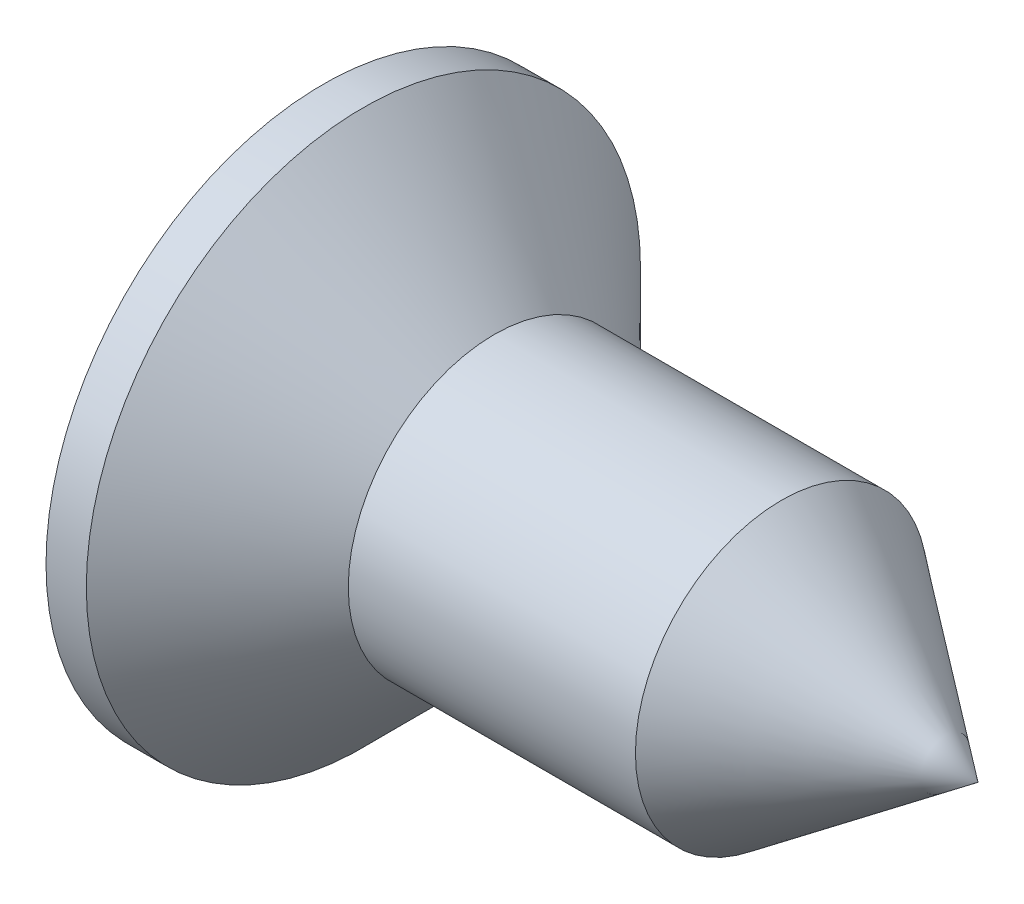
SolidWorks part; units mm, degrees
ref_plane "Front" through (0, 0, 0) normal (0, 0, 1) x (1, 0, 0)
ref_plane "Top" through (0, 0, 0) normal (0, 1, 0) x (1, 0, 0)
ref_plane "Right" through (0, 0, 0) normal (1, 0, 0) x (0, 0, -1)
sketch "Sketch1" plane through (0, 0, 0) normal (0, 0, 1) x (1, 0, 0)
  line L0 (0, 2.75) -> (0.4, 2.75)
  line L1 (0.4, 2.75) -> (1.7, 1.45)
  line L2 (1.7, 1.45) -> (6.5, 1.45)
  line L3 (6.5, 1.45) -> (6.5, 0)
  line L4 (6.5, 0) -> (0, 0)
  line L5 (0, 0) -> (0, 2.75)
  line L6 (6.6207, 0) -> (-0.9387, 0) construction
  dimension "D1" = 45
  dimension "d" = 2.9
  dimension "dK" = 5.5
  dimension "l" = 6.5
  dimension "k" = 1.7
revolve "Revolve1" add sketch "Sketch1" angle 360 about L6
cosmetic thread "ThreadCosmetic" [suppressed] parameters "D2"=2.18
chamfer "Chamfer1" distance 0.29 angle 60 1 edges at (6.5, 0, -1.45)
sketch "Sketch9" plane through (0, 0, 0) normal (0, 0, 1) x (1, 0, 0)
  line L0 (2.7022, 1.09) -> (2.0178, 1.09)
  line L1 (2.0178, 1.09) -> (1.81, 1.45)
  line L2 (2.7022, 1.09) -> (2.91, 1.45)
  line L3 (1.81, 1.45) -> (1.81, 1.7)
  line L4 (2.91, 1.45) -> (2.91, 1.7)
  line L5 (1.81, 1.7) -> (2.91, 1.7)
  line L6 (2.36, 1.09) -> (2.36, 0) construction
  line L7 (0, 0) -> (7.3035, 0) construction
  line L8 (1.7, 1.45) -> (1.7, -1.45) construction
  line L9 (5.9977, 1.45) -> (1.7, 1.45) construction
  dimension "D2" = 60
  dimension "D3" = 0.25
  dimension "advance" = 1.1
  dimension "minordia" = 2.18
  dimension "threadstart" = 0.66
revolve "ThreadSchematic" [suppressed] cut sketch "Sketch9" angle 360 about L7
pattern_linear "ThdSchPat" [suppressed] count 5 spacing 1.1 along (-1, 0, 0)
sketch "Sketch3" plane through (0, 0, 0) normal (0, 0, 1) x (1, 0, 0)
  line L0 (1.7, 1.45) -> (6.5, 1.45) construction
  line L2 (3.9, 1.45) -> (4.55, 1.45) construction
  line L3 (6.5, 1.45) -> (6.5, 0) construction
  line L4 (4.55, 1.45) -> (6.5, 1.45)
  line L5 (2.9, 0) -> (5.4301, 0) construction
  line L6 (6.5, 0) -> (6.7, 0)
  line L7 (6.7, 0) -> (6.7, 1.45)
  line L8 (6.7, 1.45) -> (6.5, 1.45)
  line L9 (4.55, 1.45) -> (6.5, 0)
  dimension "y" = 2.6
  dimension "D1" = 0.65
revolve "EndCone" cut sketch "Sketch3" angle 360 about L5
sketch "Sketch4" plane through (0, 0, 0) normal (-1, 0, 0) x (0, 0, 1)
  line L0 (-0.4, 1.6) -> (-0.4, 0.4)
  line L1 (-0.4, 1.6) -> (0.4, 1.6)
  line L2 (-1.6, 0.4) -> (-1.6, -0.4)
  line L3 (-0.4, -1.6) -> (0.4, -1.6)
  line L4 (1.6, 0.4) -> (1.6, -0.4)
  line L5 (0.4, 1.6) -> (0.4, 0.4)
  line L6 (0.4, 0.4) -> (1.6, 0.4)
  line L7 (0.4, -0.4) -> (1.6, -0.4)
  line L8 (0.4, -0.4) -> (0.4, -1.6)
  line L9 (-0.4, -0.4) -> (-0.4, -1.6)
  line L10 (-0.4, -0.4) -> (-1.6, -0.4)
  line L11 (-0.4, 0.4) -> (-1.6, 0.4)
  line L12 (1.6, 0) -> (-1.6, 0) construction
  dimension "m" = 3.2
  dimension "D1" = 0.8
extrude "Cut-Extrude1" cut sketch "Sketch4" against normal blind 1.5
draft "Draft1" type of draft neutral plane draft angle 35 faces to draft 4 face at (0.75, 0, 1.6) face at (0.75, 1.6, 0) face at (0.75, 0, -1.6) face at (0.75, -1.6, 0) neutral plane through (0, 0, 0) neutral plane normal (-1, 0, 0) parameters "D1"=35
draft "Draft2" type of draft neutral plane draft angle 8 faces to draft 8 face at (0.75, -0.7374, -0.4) face at (0.75, -0.4, -0.7374) face at (0.75, -0.4, 0.7374) face at (0.75, -0.7374, 0.4) face at (0.75, 0.7374, 0.4) face at (0.75, 0.4, 0.7374) face at (0.75, 0.4, -0.7374) face at (0.75, 0.7374, -0.4) neutral plane through (0, 0, 0) neutral plane normal (-1, 0, 0) parameters "D1"=8
sketch "Sketch6" plane through (1.5, 0, 0) normal (-1, 0, 0) x (0, 0, 1)
  line L0 (0.1892, 0.1892) -> (0.1892, 0.5497) construction
  line L1 (0.5497, 0.1892) -> (0.1892, 0.1892) construction
  line L2 (-0.1892, 0.5497) -> (-0.1892, 0.1892) construction
  line L3 (-0.1892, 0.1892) -> (-0.5497, 0.1892) construction
  line L4 (-0.5497, -0.1892) -> (-0.1892, -0.1892) construction
  line L5 (-0.1892, -0.1892) -> (-0.1892, -0.5497) construction
  line L6 (0.1892, -0.5497) -> (0.1892, -0.1892) construction
  line L7 (0.1892, -0.1892) -> (0.5497, -0.1892) construction
  line L9 (-0.3694, 0.1892) -> (-0.3694, -0.1892)
  line L10 (-0.1892, -0.3694) -> (0.1892, -0.3694)
  line L11 (0.3694, -0.1892) -> (0.3694, 0.1892)
  line L12 (0.1892, 0.3694) -> (-0.1892, 0.3694)
  arc A0 (0.1892, 0.3694) -> (0.3694, 0.1892) centre (0.3694, 0.3694) ccw
  arc A1 (-0.1892, 0.3694) -> (-0.3694, 0.1892) centre (-0.3694, 0.3694) cw
  arc A2 (-0.3694, -0.1892) -> (-0.1892, -0.3694) centre (-0.3694, -0.3694) cw
  arc A3 (0.1892, -0.3694) -> (0.3694, -0.1892) centre (0.3694, -0.3694) cw
sketch "Sketch7" plane through (0, 0, 0) normal (-1, 0, 0) x (0, 0, 1)
  line L8 (0.4, 0.4) -> (0.4, 1.6) construction
  line L9 (1.6, 0.4) -> (0.4, 0.4) construction
  line L10 (0.4, -0.4) -> (1.6, -0.4) construction
  line L11 (0.4, -1.6) -> (0.4, -0.4) construction
  line L12 (-0.4, 1.6) -> (-0.4, 0.4) construction
  line L13 (-0.4, 0.4) -> (-1.6, 0.4) construction
  line L14 (-1.6, -0.4) -> (-0.4, -0.4) construction
  line L15 (-0.4, -0.4) -> (-0.4, -1.6) construction
  line L16 (0.5802, 0.4) -> (0.5802, -0.4)
  line L17 (0.4, -0.5802) -> (-0.4, -0.5802)
  line L18 (-0.5802, -0.4) -> (-0.5802, 0.4)
  line L19 (-0.4, 0.5802) -> (0.4, 0.5802)
  arc A0 (0.4, 0.5802) -> (0.5802, 0.4) centre (0.5802, 0.5802) ccw
  arc A1 (-0.4, 0.5802) -> (-0.5802, 0.4) centre (-0.5802, 0.5802) cw
  arc A2 (-0.5802, -0.4) -> (-0.4, -0.5802) centre (-0.5802, -0.5802) cw
  arc A3 (0.1892, 0.3694) -> (0.3694, 0.1892) centre (0.3694, 0.3694) ccw construction
  arc A4 (0.5802, -0.4) -> (0.4, -0.5802) centre (0.5802, -0.5802) ccw
loft "Cut-Loft1" cut profiles "Sketch6", "Sketch7"
sketch "Sketch8" plane through (0, 0, 0) normal (-1, 0, 0) x (0, 0, 1)
  line L0 (0, 0) -> (1.6, 1.6) construction
  line L1 (0.1892, 0.3694) -> (1.6, 1.6)
  line L2 (1.6, 1.6) -> (0.3694, 0.1892)
  line L3 (0.4, 1.6) -> (1.6, 1.6) construction
  line L4 (1.6, 1.6) -> (1.6, 0.4) construction
  line L5 (0, 0) -> (0.3694, 0) construction
  line L6 (0.3694, 0.1892) -> (0.3694, 0)
  line L7 (0.1892, 0.3694) -> (0, 0.3694)
  line L8 (0, 0.3694) -> (0, 0) construction
  line L9 (0.1892, -0.3694) -> (0, -0.3694)
  line L10 (1.6, -1.6) -> (0.1892, -0.3694)
  line L11 (0.3694, -0.1892) -> (1.6, -1.6)
  line L12 (0.3694, -0.1892) -> (0.3694, 0)
  line L13 (-0.3694, -0.1892) -> (-0.3694, 0)
  line L14 (-1.6, -1.6) -> (-0.3694, -0.1892)
  line L15 (-0.1892, -0.3694) -> (-1.6, -1.6)
  line L16 (-0.1892, -0.3694) -> (0, -0.3694)
  line L17 (-0.1892, 0.3694) -> (0, 0.3694)
  line L18 (-1.6, 1.6) -> (-0.1892, 0.3694)
  line L19 (-0.3694, 0.1892) -> (-1.6, 1.6)
  line L20 (-0.3694, 0.1892) -> (-0.3694, 0)
  arc A1 (0.1892, 0.3694) -> (0.3694, 0.1892) centre (0.3694, 0.3694) ccw construction
  arc A2 (0.1892, 0.3694) -> (0.3694, 0.1892) centre (0.3694, 0.3694) ccw construction
extrude "TypeZ" [suppressed] cut sketch "Sketch8" against normal blind 0.3 draft 3
equation "\"D1@Chamfer1\" = \"d@Sketch1\" / 10"
equation "\"D1@Sketch4\" = \"m@Sketch4\" / 4"
equation "\"D1@TypeZ\" = \"p@Cut-Extrude1\"*0.2"
equation "\"D1@Sketch3\" = \"y@Sketch3\" / 4"
equation "\"threadstart@Sketch9\"=\"advance@Sketch9\"*0.6"
equation "\"D1@ThdSchPat\" = int(((\"l@Sketch1\"-\"k@Sketch1\")/\"advance@Sketch9\") + 0.999)"
equation "\"D3@ThdSchPat\" = \"advance@Sketch9\""
equation "\"minordia@Sketch9\" = \"D2@ThreadCosmetic\""
